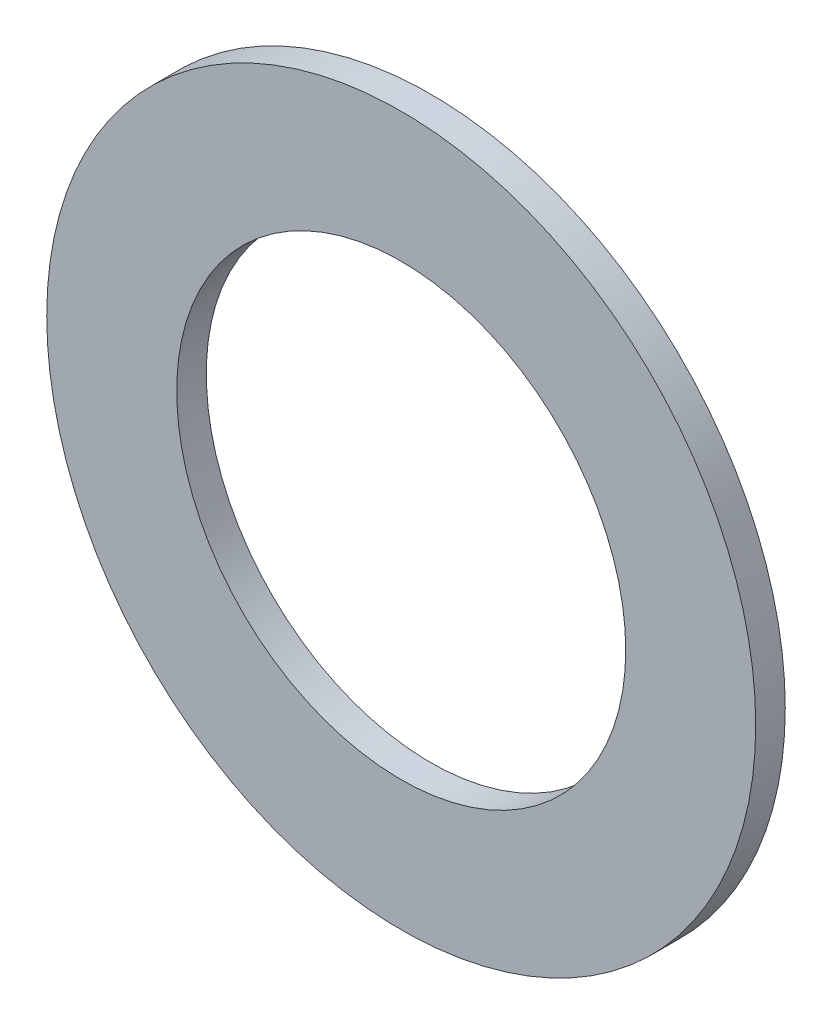
SolidWorks part; units mm, degrees
material "1.0406 (C25)"
ref_plane "Płaszczyzna przednia" through (0, 0, 0) normal (0, 0, 1) x (1, 0, 0)
ref_plane "Płaszczyzna górna" through (0, 0, 0) normal (0, 1, 0) x (1, 0, 0)
ref_plane "Płaszczyzna prawa" through (0, 0, 0) normal (1, 0, 0) x (0, 0, -1)
sketch "Szkic1" plane through (0, 0, 0) normal (0, 0, 1) x (1, 0, 0)
  circle A0 centre (0, 0) radius 7.6
  circle A1 centre (0, 0) radius 12
  dimension "D1" = 15.2
  dimension "D2" = 24
extrude "Dodanie-wyciągnięcie1" add sketch "Szkic1" along normal blind 1
